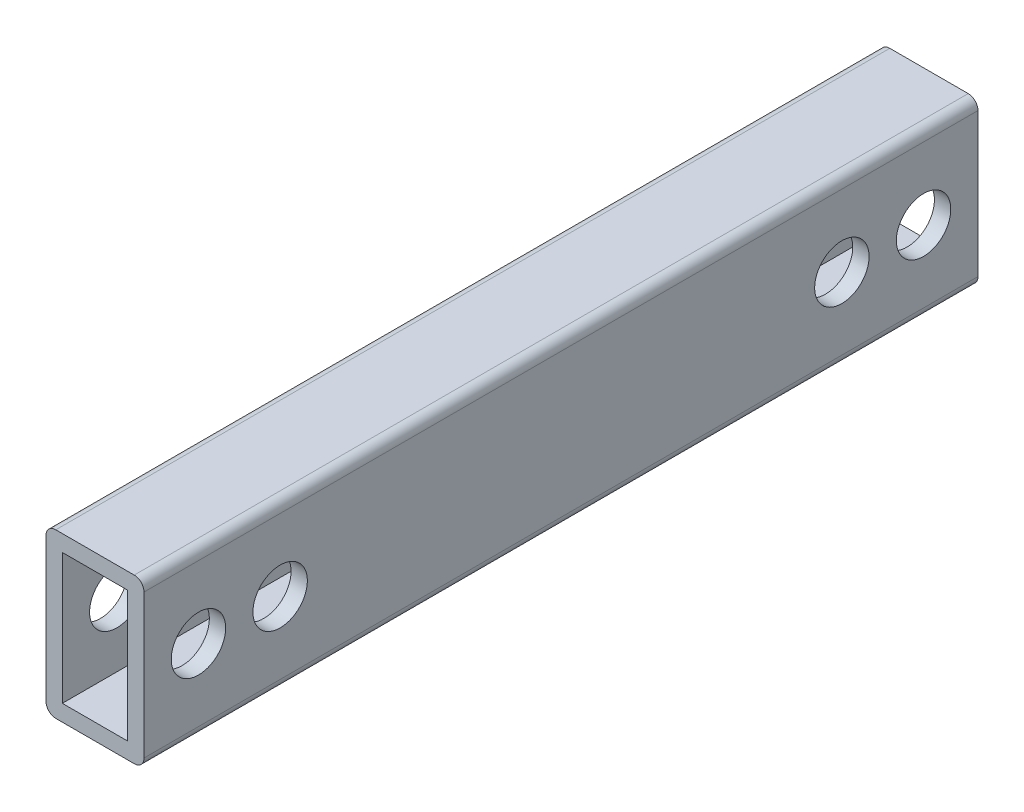
SolidWorks part; units mm, degrees
material "6061-T6 (SS)"
ref_plane "Front Plane" through (0, 0, 0) normal (0, 0, 1) x (1, 0, 0)
ref_plane "Top Plane" through (0, 0, 0) normal (0, 1, 0) x (1, 0, 0)
ref_plane "Right Plane" through (0, 0, 0) normal (1, 0, 0) x (0, 0, -1)
sketch "Sketch1" plane through (0, 0, 0) normal (0, 0, 1) x (1, 0, 0)
  line L1 (9, -15) -> (-9, -15)
  line L2 (9, -15) -> (9, 15)
  line L3 (9, 15) -> (-9, 15)
  line L4 (-9, -15) -> (-9, 15)
  line L5 (9, -15) -> (-9, 15) construction
  line L6 (9, 15) -> (-9, -15) construction
  line L7 (6, -12) -> (-6, -12)
  line L8 (6, -12) -> (6, 12)
  line L9 (6, 12) -> (-6, 12)
  line L10 (-6, -12) -> (-6, 12)
  line L11 (6, -12) -> (-6, 12) construction
  line L12 (6, 12) -> (-6, -12) construction
  point P0 (0, 0)
  point P6 (0, 0)
  dimension "D1" = 30
  dimension "D2" = 18
  dimension "D3" = 3
  dimension "D4" = 3
extrude "Body" add sketch "Sketch1" along normal blind 153.157
sketch "Sketch2" plane through (9, 0, 0) normal (1, 0, 0) x (0, 0, -1)
  line L0 (0, 0) -> (-153.157, 0) construction
  line L1 (-153.157, -15) -> (-153.157, 15) construction
  line L2 (-76.5785, -15) -> (-76.5785, 15) construction
  line L3 (-153.157, -15) -> (0, -15) construction
  line L4 (-153.157, 15) -> (0, 15) construction
  circle A0 centre (-143.157, 0) radius 5
  circle A1 centre (-128.157, 0) radius 5
  circle A2 centre (-25, 0) radius 5
  circle A3 centre (-10, 0) radius 5
  dimension "D1" = 10
  dimension "D2" = 10
  dimension "D3" = 10
  dimension "D4" = 15
extrude "Mount Holes" cut sketch "Sketch2" against normal through all
fillet "Corner Fillets" radius 1.8 4 edges at (-9, -15, 76.5785) (9, -15, 76.5785) (9, 15, 76.5785) (-9, 15, 76.5785)
equation "\"linkage_thickness\"= 18.0mm"
equation "\"width\"= 30.0mm"
equation "\"wall_thickness\"= 3.0mm"
equation "\"length\"= 153.15701543058677mm"
equation "\"angle\"= 5.501757111213453"
equation "\"bolt_diameter\"= 10.0mm"
equation "\"bolt_spacing\"= 5.0mm"
equation "\"D1@Sketch1\"=\"width\""
equation "\"D2@Sketch1\"=\"linkage_thickness\""
equation "\"D3@Sketch1\"=\"wall_thickness\""
equation "\"D4@Sketch1\"=\"wall_thickness\""
equation "\"D1@Body\"=\"length\""
equation "\"D1@Sketch2\"=\"bolt_diameter\""
equation "\"D2@Sketch2\"=\"bolt_diameter\""
equation "\"D3@Sketch2\"=\"bolt_spacing\"+\"bolt_diameter\"/2"
equation "\"D4@Sketch2\"=\"bolt_spacing\"+\"bolt_diameter\""
equation "\"D1@Corner Fillets\"=\"linkage_thickness\"/10"
